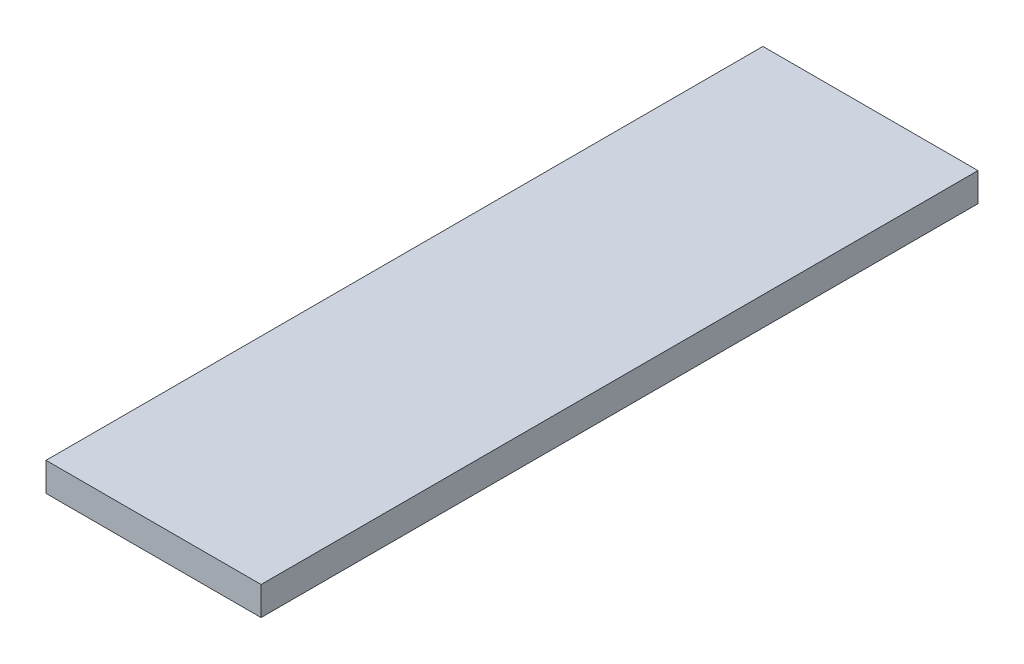
SolidWorks part; units mm, degrees
ref_plane "Front Plane" through (0, 0, 0) normal (0, 0, 1) x (1, 0, 0)
ref_plane "Top Plane" through (0, 0, 0) normal (0, 1, 0) x (1, 0, 0)
ref_plane "Right Plane" through (0, 0, 0) normal (1, 0, 0) x (0, 0, -1)
sketch "Sketch1" plane through (0, 0, 0) normal (0, 0, 1) x (1, 0, 0)
  line L1 (0, 0) -> (150, 0)
  line L2 (0, 0) -> (0, 20)
  line L3 (0, 20) -> (150, 20)
  line L4 (150, 0) -> (150, 20)
  dimension "D1" = 150
  dimension "D2" = 20
extrude "Boss-Extrude1" add sketch "Sketch1" along normal blind 500
